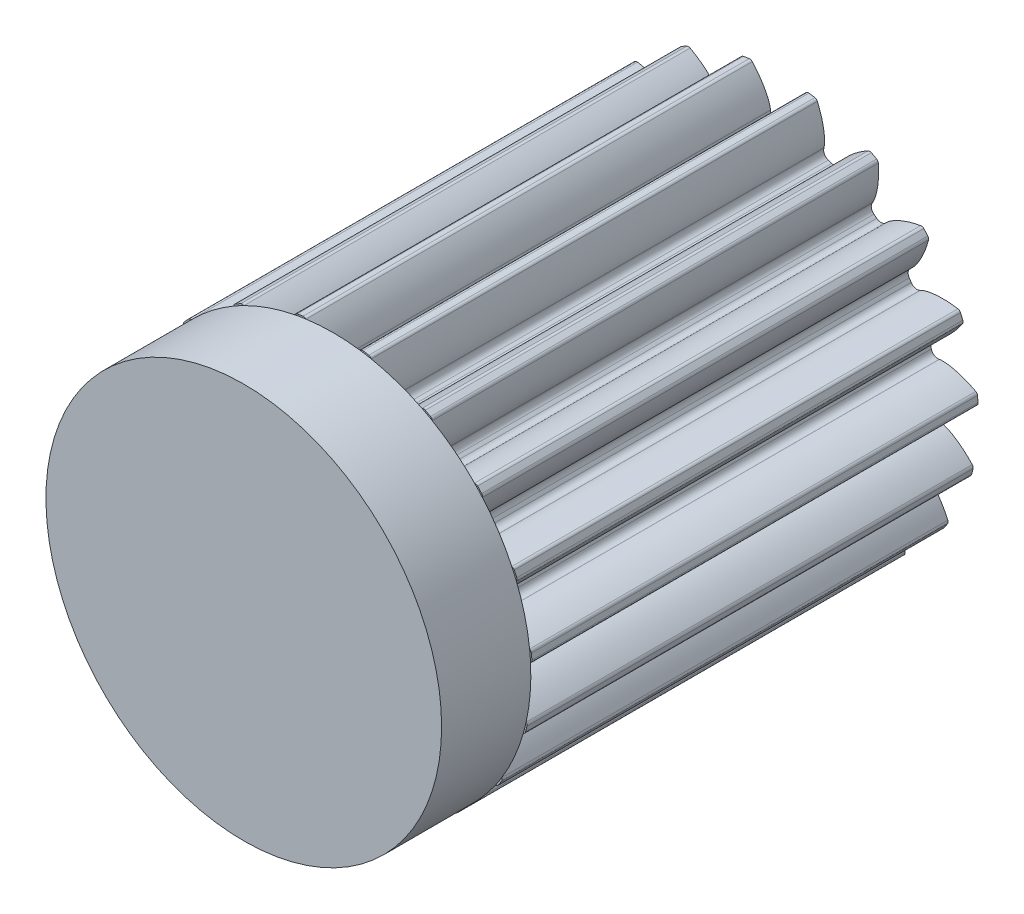
SolidWorks part; units mm, degrees
material "Alloy Steel"
ref_plane "Front" through (0, 0, 0) normal (0, 0, 1) x (1, 0, 0)
ref_plane "Top" through (0, 0, 0) normal (0, 1, 0) x (1, 0, 0)
ref_plane "Right" through (0, 0, 0) normal (1, 0, 0) x (0, 0, -1)
sketch "Sketch1" plane through (0, 0, 0) normal (0, 0, 1) x (1, 0, 0)
  circle A0 centre (0, 0) radius 5.6745
extrude "Boss-Extrude1" add sketch "Sketch1" along normal blind 12.7
sketch "Sketch3" plane through (0, 0, 0) normal (0, 0, 1) x (1, 0, 0)
  line L0 (0, 0) -> (43.7181, 0) construction
  line L2 (0, 0) -> (-0.2348, 4.4523) construction
  line L3 (0, 0) -> (0.2348, 4.4523) construction
  line L4 (0.2348, 4.4523) -> (0.2451, 4.6466) construction
  line L5 (0, 0) -> (0, 61.276) construction
  line L6 (-0.2348, 4.4523) -> (-0.2451, 4.6466) construction
  circle A0 centre (0, 0) radius 5.6745 construction
  circle A1 centre (0, 0) radius 5.134 construction
  circle A2 centre (0, 0) radius 4.653 construction
  arc A3 (0.2348, 4.4523) -> (-0.2348, 4.4523) centre (0, 0) ccw construction
  arc A5 (0.7993, 5.6179) -> (-0.7993, 5.6179) centre (0, 0) ccw
  spline S0 degree 4 poles (-0.2451, 4.6466) (-0.2452, 4.6482) (-0.2456, 4.6529) (-0.2466, 4.6618) (-0.2488, 4.6761) (-0.2521, 4.6944) (-0.2572, 4.7178) (-0.264, 4.7454) (-0.2725, 4.7754) (-0.2828, 4.8079) (-0.294, 4.8402) (-0.306, 4.8721) (-0.3187, 4.9038) (-0.3349, 4.9419) (-0.3557, 4.9873) (-0.3817, 5.0398) (-0.4133, 5.0987) (-0.4478, 5.1579) (-0.4835, 5.2156) (-0.5216, 5.2731) (-0.5599, 5.3281) (-0.6018, 5.3844) (-0.6415, 5.4359) (-0.6883, 5.4927) (-0.7267, 5.5382) (-0.7797, 5.597) (-0.8117, 5.6314) (-0.85, 5.6713) (-0.8674, 5.6888) (-0.8781, 5.6996) knots 0 0 0 0 0 0.005377 0.015084 0.028532 0.04661 0.064855 0.092111 0.119476 0.146842 0.174209 0.201575 0.228941 0.256307 0.307035 0.361767 0.4165 0.471232 0.525964 0.580697 0.635429 0.690161 0.744894 0.799626 0.854358 0.909091 0.954545 1 1 1 1 1 construction
  spline S1 degree 4 poles (-0.2451, 4.6466) (-0.2452, 4.6482) (-0.2456, 4.6529) (-0.2466, 4.6618) (-0.2488, 4.6761) (-0.2521, 4.6944) (-0.2572, 4.7178) (-0.264, 4.7454) (-0.2725, 4.7754) (-0.2828, 4.8079) (-0.294, 4.8402) (-0.306, 4.8721) (-0.3187, 4.9038) (-0.3349, 4.9419) (-0.3557, 4.9873) (-0.3817, 5.0398) (-0.4133, 5.0987) (-0.4478, 5.1579) (-0.4835, 5.2156) (-0.5216, 5.2731) (-0.5599, 5.3281) (-0.6018, 5.3844) (-0.6415, 5.4359) (-0.6883, 5.4927) (-0.7267, 5.5382) (-0.7682, 5.5843) (-0.7887, 5.6066) (-0.7993, 5.6179) knots 0 0 0 0 0 0.005377 0.015084 0.028532 0.04661 0.064855 0.092111 0.119476 0.146842 0.174209 0.201575 0.228941 0.256307 0.307035 0.361767 0.4165 0.471232 0.525964 0.580697 0.635429 0.690161 0.744894 0.799626 0.854358 0.909091 0.909091 0.909091 0.909091 0.909091
  spline S2 degree 4 poles (0.2451, 4.6466) (0.2452, 4.6482) (0.2456, 4.6529) (0.2466, 4.6618) (0.2488, 4.6761) (0.2521, 4.6944) (0.2572, 4.7178) (0.264, 4.7454) (0.2725, 4.7754) (0.2828, 4.8079) (0.294, 4.8402) (0.306, 4.8721) (0.3187, 4.9038) (0.3349, 4.9419) (0.3557, 4.9873) (0.3817, 5.0398) (0.4133, 5.0987) (0.4478, 5.1579) (0.4835, 5.2156) (0.5216, 5.2731) (0.5599, 5.3281) (0.6018, 5.3844) (0.6415, 5.4359) (0.6883, 5.4927) (0.7267, 5.5382) (0.7797, 5.597) (0.8117, 5.6314) (0.85, 5.6713) (0.8674, 5.6888) (0.8781, 5.6996) knots 0 0 0 0 0 0.005377 0.015084 0.028532 0.04661 0.064855 0.092111 0.119476 0.146842 0.174209 0.201575 0.228941 0.256307 0.307035 0.361767 0.4165 0.471232 0.525964 0.580697 0.635429 0.690161 0.744894 0.799626 0.854358 0.909091 0.954545 1 1 1 1 1 construction
  spline S3 degree 4 poles (0.2451, 4.6466) (0.2452, 4.6482) (0.2456, 4.6529) (0.2466, 4.6618) (0.2488, 4.6761) (0.2521, 4.6944) (0.2572, 4.7178) (0.264, 4.7454) (0.2725, 4.7754) (0.2828, 4.8079) (0.294, 4.8402) (0.306, 4.8721) (0.3187, 4.9038) (0.3349, 4.9419) (0.3557, 4.9873) (0.3817, 5.0398) (0.4133, 5.0987) (0.4478, 5.1579) (0.4835, 5.2156) (0.5216, 5.2731) (0.5599, 5.3281) (0.6018, 5.3844) (0.6415, 5.4359) (0.6883, 5.4927) (0.7267, 5.5382) (0.7682, 5.5843) (0.7887, 5.6066) (0.7993, 5.6179) knots 0 0 0 0 0 0.005377 0.015084 0.028532 0.04661 0.064855 0.092111 0.119476 0.146842 0.174209 0.201575 0.228941 0.256307 0.307035 0.361767 0.4165 0.471232 0.525964 0.580697 0.635429 0.690161 0.744894 0.799626 0.854358 0.909091 0.909091 0.909091 0.909091 0.909091
  point P0 (0, 4.4585)
sketch "DCLTBC" plane through (0, 0, 0) normal (0, 0, 1) x (1, 0, 0)
  line L0 (0, 0) -> (41.04, 0) construction
  line L1 (-0.2348, 4.4523) -> (-0.2451, 4.6466) construction
  line L2 (0.2348, 4.4523) -> (0.2451, 4.6466) construction
  line L3 (-0.2348, 4.4523) -> (-0.2451, 4.6466)
  line L4 (0.2348, 4.4523) -> (0.2451, 4.6466)
  line L5 (0, 0) -> (0, 104.9356) construction
  circle A0 centre (0, 0) radius 5.6745
  circle A1 centre (0, 0) radius 5.134 construction
  circle A2 centre (0, 0) radius 4.653 construction
  arc A3 (0.2348, 4.4523) -> (-0.2348, 4.4523) centre (0, 0) ccw construction
  arc A4 (0.2348, 4.4523) -> (-0.2348, 4.4523) centre (0, 0) ccw
  spline S0 degree 4 poles (-997.9315, -62.9973) (-10.2621, 3.4389) (-0.3548, 4.1906) (-0.2142, 4.4429) (-0.2488, 4.6761) (-0.2521, 4.6944) (-0.2572, 4.7178) (-0.264, 4.7454) (-0.2725, 4.7754) (-0.2828, 4.8079) (-0.294, 4.8402) (-0.306, 4.8721) (-0.3187, 4.9038) (-0.3349, 4.9419) (-0.3557, 4.9873) (-0.3817, 5.0398) (-0.4133, 5.0987) (-0.4478, 5.1579) (-0.4835, 5.2156) (-0.5216, 5.2731) (-0.5599, 5.3281) (-0.6018, 5.3844) (-0.6415, 5.4359) (-0.6883, 5.4927) (-0.9196, 5.7667) (-1.8953, 6.7396) (13.8141, -10.2275) (-683.1336, 736.6213) knots -0.709711 -0.709711 -0.709711 -0.709711 -0.709711 0.005377 0.015084 0.028532 0.04661 0.064855 0.092111 0.119476 0.146842 0.174209 0.201575 0.228941 0.256307 0.307035 0.361767 0.4165 0.471232 0.525964 0.580697 0.635429 0.690161 0.744894 0.799626 0.854358 2.008996 2.008996 2.008996 2.008996 2.008996 only from (-0.2451, 4.6466) to (-0.7993, 5.6179) construction
  spline S1 degree 4 poles (997.9315, -62.9973) (10.2621, 3.4389) (0.3548, 4.1906) (0.2142, 4.4429) (0.2488, 4.6761) (0.2521, 4.6944) (0.2572, 4.7178) (0.264, 4.7454) (0.2725, 4.7754) (0.2828, 4.8079) (0.294, 4.8402) (0.306, 4.8721) (0.3187, 4.9038) (0.3349, 4.9419) (0.3557, 4.9873) (0.3817, 5.0398) (0.4133, 5.0987) (0.4478, 5.1579) (0.4835, 5.2156) (0.5216, 5.2731) (0.5599, 5.3281) (0.6018, 5.3844) (0.6415, 5.4359) (0.6883, 5.4927) (0.9196, 5.7667) (1.8953, 6.7396) (-13.8141, -10.2275) (683.1336, 736.6213) knots -0.709711 -0.709711 -0.709711 -0.709711 -0.709711 0.005377 0.015084 0.028532 0.04661 0.064855 0.092111 0.119476 0.146842 0.174209 0.201575 0.228941 0.256307 0.307035 0.361767 0.4165 0.471232 0.525964 0.580697 0.635429 0.690161 0.744894 0.799626 0.854358 2.008996 2.008996 2.008996 2.008996 2.008996 only from (0.2451, 4.6466) to (0.7993, 5.6179) construction
  spline S2 degree 4 poles (-0.2451, 4.6466) (-0.2452, 4.6482) (-0.2456, 4.6529) (-0.2466, 4.6618) (-0.2488, 4.6761) (-0.2521, 4.6944) (-0.2572, 4.7178) (-0.264, 4.7454) (-0.2725, 4.7754) (-0.2828, 4.8079) (-0.294, 4.8402) (-0.306, 4.8721) (-0.3187, 4.9038) (-0.3349, 4.9419) (-0.3557, 4.9873) (-0.3817, 5.0398) (-0.4133, 5.0987) (-0.4478, 5.1579) (-0.4835, 5.2156) (-0.5216, 5.2731) (-0.5599, 5.3281) (-0.6018, 5.3844) (-0.6415, 5.4359) (-0.6883, 5.4927) (-0.7267, 5.5382) (-0.7682, 5.5843) (-0.7887, 5.6066) (-0.7993, 5.6179) knots 0 0 0 0 0 0.005377 0.015084 0.028532 0.04661 0.064855 0.092111 0.119476 0.146842 0.174209 0.201575 0.228941 0.256307 0.307035 0.361767 0.4165 0.471232 0.525964 0.580697 0.635429 0.690161 0.744894 0.799626 0.854358 0.909091 0.909091 0.909091 0.909091 0.909091
  spline S3 degree 4 poles (0.2451, 4.6466) (0.2452, 4.6482) (0.2456, 4.6529) (0.2466, 4.6618) (0.2488, 4.6761) (0.2521, 4.6944) (0.2572, 4.7178) (0.264, 4.7454) (0.2725, 4.7754) (0.2828, 4.8079) (0.294, 4.8402) (0.306, 4.8721) (0.3187, 4.9038) (0.3349, 4.9419) (0.3557, 4.9873) (0.3817, 5.0398) (0.4133, 5.0987) (0.4478, 5.1579) (0.4835, 5.2156) (0.5216, 5.2731) (0.5599, 5.3281) (0.6018, 5.3844) (0.6415, 5.4359) (0.6883, 5.4927) (0.7267, 5.5382) (0.7682, 5.5843) (0.7887, 5.6066) (0.7993, 5.6179) knots 0 0 0 0 0 0.005377 0.015084 0.028532 0.04661 0.064855 0.092111 0.119476 0.146842 0.174209 0.201575 0.228941 0.256307 0.307035 0.361767 0.4165 0.471232 0.525964 0.580697 0.635429 0.690161 0.744894 0.799626 0.854358 0.909091 0.909091 0.909091 0.909091 0.909091
extrude "Cut-Extrude-DCLTBC" cut sketch "DCLTBC" along normal through all
fillet "Fillet-Tip-DCLTBC" radius 0.0961 2 edges at (0.7993, 5.6179, 6.35) (-0.7993, 5.6179, 6.35)
fillet "Fillet-Root-DCLTBC" radius 0.1922 2 edges at (-0.2348, 4.4523, 6.35) (0.2348, 4.4523, 6.35)
pattern_circular "CirPattern-DCLTBC" count 19 over 360 about axis through (0, 0, 12.7) along (0, 0, 1) of "Cut-Extrude-DCLTBC", "Fillet-Tip-DCLTBC", "Fillet-Root-DCLTBC"
sketch "DCGTBC" [suppressed] plane through (0, 0, 0) normal (0, 0, 1) x (1, 0, 0)
  line L0 (0, 0) -> (41.04, 0) construction
  line L1 (-48.5645, 4.2488) -> (0, 0) construction
  line L2 (0, 0) -> (48.5645, 4.2488) construction
  line L3 (0, 0) -> (-16.5124, 0)
  line L5 (0, 0) -> (0, 104.9356) construction
  circle A0 centre (0, 0) radius 51
  circle A1 centre (0, 0) radius 50 construction
  circle A2 centre (0, 0) radius 45.3154 construction
  arc A3 (-0.6955, 48.745) -> (0.6955, 48.745) centre (0, 0) ccw construction
  arc A11 (48.5645, 4.2488) -> (-48.5645, 4.2488) centre (0, 0) ccw
  spline S4 degree 4 poles (999.295, 35.0053) (13.8403, 43.0294) (-0.3845, 43.6678) (-0.691, 44.5628) (-0.6404, 45.4695) (-0.6324, 45.568) (-0.6192, 45.6953) (-0.6, 45.8451) (-0.575, 46.0098) (-0.5436, 46.1888) (-0.5087, 46.3672) (-0.4704, 46.545) (-0.4291, 46.7221) (-0.3755, 46.9363) (-0.3062, 47.1929) (-0.2177, 47.4924) (-0.1086, 47.8314) (0.0119, 48.1762) (0.1381, 48.5148) (0.2744, 48.8561) (0.4125, 49.1858) (0.565, 49.5274) (0.7103, 49.8422) (0.8831, 50.1938) (1.4894, 51.401) (3.4482, 54.802) (-14.0283, 22.6362) (482.937, 927.3456) knots -0.499953 -0.499953 -0.499953 -0.499953 -0.499953 0.005377 0.015084 0.028532 0.04661 0.064855 0.092111 0.119476 0.146842 0.174209 0.201575 0.228941 0.256307 0.307035 0.361767 0.4165 0.471232 0.525964 0.580697 0.635429 0.690161 0.744894 0.799626 0.854358 1.622574 1.622574 1.622574 1.622574 1.622574 only from (-0.6465, 45.3108) to (1.2974, 50.9835) construction
  spline S5 degree 4 poles (-999.295, 35.0053) (-13.8403, 43.0294) (0.3845, 43.6678) (0.691, 44.5628) (0.6404, 45.4695) (0.6324, 45.568) (0.6192, 45.6953) (0.6, 45.8451) (0.575, 46.0098) (0.5436, 46.1888) (0.5087, 46.3672) (0.4704, 46.545) (0.4291, 46.7221) (0.3755, 46.9363) (0.3062, 47.1929) (0.2177, 47.4924) (0.1086, 47.8314) (-0.0119, 48.1762) (-0.1381, 48.5148) (-0.2744, 48.8561) (-0.4125, 49.1858) (-0.565, 49.5274) (-0.7103, 49.8422) (-0.8831, 50.1938) (-1.4894, 51.401) (-3.4482, 54.802) (14.0283, 22.6362) (-482.937, 927.3456) knots -0.499953 -0.499953 -0.499953 -0.499953 -0.499953 0.005377 0.015084 0.028532 0.04661 0.064855 0.092111 0.119476 0.146842 0.174209 0.201575 0.228941 0.256307 0.307035 0.361767 0.4165 0.471232 0.525964 0.580697 0.635429 0.690161 0.744894 0.799626 0.854358 1.622574 1.622574 1.622574 1.622574 1.622574 only from (0.6465, 45.3108) to (-1.2974, 50.9835) construction
  spline S6 degree 4 poles (-0.6465, 45.3108) (-0.6465, 45.3197) (-0.6463, 45.3448) (-0.6447, 45.3921) (-0.6404, 45.4695) (-0.6324, 45.568) (-0.6192, 45.6953) (-0.6, 45.8451) (-0.575, 46.0098) (-0.5436, 46.1888) (-0.5087, 46.3672) (-0.4704, 46.545) (-0.4291, 46.7221) (-0.3755, 46.9363) (-0.3062, 47.1929) (-0.2177, 47.4924) (-0.1086, 47.8314) (0.0119, 48.1762) (0.1381, 48.5148) (0.2744, 48.8561) (0.4125, 49.1858) (0.565, 49.5274) (0.7103, 49.8422) (0.8831, 50.1938) (1.0255, 50.4773) (1.1808, 50.7691) (1.2577, 50.911) (1.2974, 50.9835) knots 0 0 0 0 0 0.005377 0.015084 0.028532 0.04661 0.064855 0.092111 0.119476 0.146842 0.174209 0.201575 0.228941 0.256307 0.307035 0.361767 0.4165 0.471232 0.525964 0.580697 0.635429 0.690161 0.744894 0.799626 0.854358 0.909091 0.909091 0.909091 0.909091 0.909091
  spline S7 degree 4 poles (0.6465, 45.3108) (0.6465, 45.3197) (0.6463, 45.3448) (0.6447, 45.3921) (0.6404, 45.4695) (0.6324, 45.568) (0.6192, 45.6953) (0.6, 45.8451) (0.575, 46.0098) (0.5436, 46.1888) (0.5087, 46.3672) (0.4704, 46.545) (0.4291, 46.7221) (0.3755, 46.9363) (0.3062, 47.1929) (0.2177, 47.4924) (0.1086, 47.8314) (-0.0119, 48.1762) (-0.1381, 48.5148) (-0.2744, 48.8561) (-0.4125, 49.1858) (-0.565, 49.5274) (-0.7103, 49.8422) (-0.8831, 50.1938) (-1.0255, 50.4773) (-1.1808, 50.7691) (-1.2577, 50.911) (-1.2974, 50.9835) knots 0 0 0 0 0 0.005377 0.015084 0.028532 0.04661 0.064855 0.092111 0.119476 0.146842 0.174209 0.201575 0.228941 0.256307 0.307035 0.361767 0.4165 0.471232 0.525964 0.580697 0.635429 0.690161 0.744894 0.799626 0.854358 0.909091 0.909091 0.909091 0.909091 0.909091
  dimension "D1" = 5
  dimension "D2" = 5
extrude "Cut-Extrude-DCGTBC" [suppressed] cut sketch "DCGTBC" along normal through all
fillet "Fillet-Tip-DCGTBC" [suppressed] radius 0.0961
pattern_circular "CirPattern-DCGTBC" [suppressed] count 19 over 360
sketch "Sketch4" plane through (0, 0, 12.7) normal (0, 0, 1) x (1, 0, 0)
  circle A0 centre (0, 0) radius 5.6319
extrude "Boss-Extrude2" add sketch "Sketch4" along normal blind 2.54
equation "\"DiametralPitch\"= 47'Diametral Pitch"
equation "\"NumTeeth\" = 19'Number of Teeth"
equation "\"PressureAngle\"= 25deg'Pressure Angle"
equation "\"Addendum\"= 1 / \"DiametralPitch\"'Addendum"
equation "\"Dedendum\"= 1.25 / \"DiametralPitch\"'Dedendum"
equation "\"WorkingDepth\"= 2 / \"DiametralPitch\"'Working Depth - here for REF (Not used in building model)"
equation "\"WholeDepth\"= 2.25 / \"DiametralPitch\"'Whole Depth - here for REF (Not used in building model)"
equation "\"Clearance\"= .25 / \"DiametralPitch\"'Clearance"
equation "\"CircularPitch\"= pi / \"DiametralPitch\"'Circular Pitch - here for REF (Not used in building model)"
equation "\"PitchCircle\"= \"NumTeeth\" / \"DiametralPitch\"'Pitch Circle - or - Pitch Diameter"
equation "\"OutsideDiameter\"= ( \"NumTeeth\" + 2 ) / \"DiametralPitch\"'Outside Diameter"
equation "\"Fillet_Root\"= \"Clearance\" * cos ( \"PressureAngle\" ) * tan ( ( 90 + \"PressureAngle\" ) / 2 ) 'Fillet Root"
equation "\"AddendumCircle\"= \"PitchCircle\" + ( 2 * \"Addendum\" )'Addendum Circle - or - Addendum Diameter"
equation "\"DedendumCircle\"= \"PitchCircle\" - ( 2 * \"Dedendum\" )'Dedendum Circle - or - Dedendum Diameter"
equation "\"BaseCircle\"= \"PitchCircle\" * cos ( \"PressureAngle\" )'Base Circle - Base Diameter"
equation "\"PitchAngle\"= 360deg / \"NumTeeth\"'Pitch Angle"
equation "\"Alpha\"= sqr ( \"PitchCircle\" ^ 2 - \"BaseCircle\" ^ 2 ) / \"BaseCircle\" * 180 / PI - \"PressureAngle\"'Alpha - Used for Calculating Beta"
equation "\"Beta\"= ( \"PitchAngle\" / 4 - ( \"Alpha\" - 90 ) )'Beta - Used in definition of the parameters for the parametric equation driven curve"
equation "\"Gamma\"= ( \"PitchAngle\" / 4 - ( \"Alpha\" + 90 ) )'Gamma - Used in definition of the parameters for the parametric equation driven curve"
equation "\"Phi\"= sqr ( ( \"AddendumCircle\" / 2 ) ^ 2 - ( \"BaseCircle\" / 2 ) ^ 2 ) / ( \"BaseCircle\" / 2 )'Phi - Used in definition of the parameters for the parametric equation driven curve"
equation "\"DCGTBC\"= iif ( \"DedendumCircle\" > \"BaseCircle\" , \"unsuppressed\" , \"suppressed\" )'if Dedendum Circle IS GREATER THAN BaseCircle THEN UnsuppressORSuppress FEATURE"
equation "\"DCLTBC\"= iif ( \"DedendumCircle\" - .002 > \"BaseCircle\" , \"suppressed\" , \"unsuppressed\" )'if Dedendum Circle - .002 IS GREATER THAN BaseCircle THEN SuppressORUnsuppress FEATURE"
equation "\"Cut-Extrude-DCGTBC\"= iif ( \"DedendumCircle\" > \"BaseCircle\" , \"unsuppressed\" , \"suppressed\" )'if Dedendum Circle IS GREATER THAN BaseCircle THEN UnsuppressORSuppress FEATURE"
equation "\"Cut-Extrude-DCLTBC\"= iif ( \"DedendumCircle\" - .002 > \"BaseCircle\" , \"suppressed\" , \"unsuppressed\" )'if Dedendum Circle - .002 IS GREATER THAN BaseCircle THEN SuppressORUnsuppress FEATURE"
equation "\"CirPattern-DCGTBC\"= iif ( \"DedendumCircle\" > \"BaseCircle\" , \"unsuppressed\" , \"suppressed\" )'if Dedendum Circle IS GREATER THAN BaseCircle THEN UnsuppressORSuppress FEATURE"
equation "\"CirPattern-DCLTBC\"= iif ( \"DedendumCircle\" - .002 > \"BaseCircle\" , \"suppressed\" , \"unsuppressed\" )'if Dedendum Circle - .002 IS GREATER THAN BaseCircle THEN SuppressORUnsuppress FEATURE"
equation "\"Fillet-Tip-DCGTBC\"= iif ( \"DedendumCircle\" > \"BaseCircle\" , \"unsuppressed\" , \"suppressed\" )'if Dedendum Circle IS GREATER THAN BaseCircle THEN UnsuppressORSuppress FEATURE"
equation "\"Fillet-Tip-DCLTBC\"= iif ( \"DedendumCircle\" - .002 > \"BaseCircle\" , \"suppressed\" , \"unsuppressed\" )'if Dedendum Circle - .002 IS GREATER THAN BaseCircle THEN SuppressORUnsuppress FEATURE"
equation "\"Fillet-Root-DCLTBC\"= iif ( \"DedendumCircle\" - .002 > \"BaseCircle\" , \"suppressed\" , \"unsuppressed\" )'if Dedendum Circle - .002 IS GREATER THAN BaseCircle THEN SuppressORUnsuppress FEATURE"
equation "\"D1@CirPattern-DCGTBC\"= \"NumTeeth\"'Number of Teeth"
equation "\"D1@CirPattern-DCLTBC\"= \"NumTeeth\"'Number of Teeth"
equation "\"D1@Fillet-Tip-DCGTBC\"= \"Fillet_Root\" / 2 'Tip Rad For Large No of Teeth"
equation "\"D1@Fillet-Tip-DCLTBC\"=\"Fillet_Root\" / 2'Tip Rad For Small No of Teeth"
equation "\"D1@Fillet-Root-DCLTBC\"= \"Fillet_Root\"'Fillet Root"
